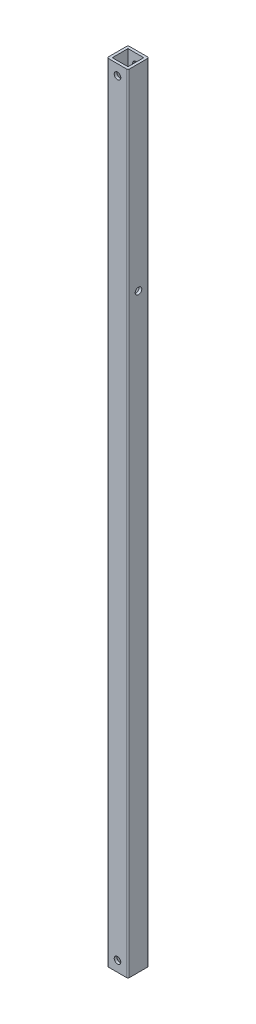
SolidWorks part; units mm, degrees
ref_plane "Front Plane" through (0, 0, 0) normal (0, 0, 1) x (1, 0, 0)
ref_plane "Top Plane" through (0, 0, 0) normal (0, 1, 0) x (1, 0, 0)
ref_plane "Right Plane" through (0, 0, 0) normal (1, 0, 0) x (0, 0, -1)
sketch "Sketch1" plane through (0, 0, 0) normal (0, 1, 0) x (1, 0, 0)
  line L0 (-2.7217, 3.211) -> (-2.7217, -8.789)
  line L1 (-4.7217, 5.211) -> (11.2783, 5.211)
  line L2 (-4.7217, 5.211) -> (-4.7217, -10.789)
  line L3 (-4.7217, -10.789) -> (11.2783, -10.789)
  line L4 (11.2783, 5.211) -> (11.2783, -10.789)
  line L5 (-2.7217, -8.789) -> (9.2783, -8.789)
  line L6 (9.2783, 3.211) -> (9.2783, -8.789)
  line L7 (-2.7217, 3.211) -> (9.2783, 3.211)
  dimension "D1" = 16
  dimension "D2" = 16
  dimension "D3" = 2
extrude "Boss-Extrude1" add sketch "Sketch1" along normal blind 600
fillet "Fillet1" radius 1 4 edges at (11.2783, 300, -5.211) (-4.7217, 300, -5.211) (-4.7217, 300, 10.789) (11.2783, 300, 10.789)
sketch "Sketch2" plane through (0, 0, 10.789) normal (0, 0, 1) x (1, 0, 0)
  line L0 (-3.7217, 600) -> (10.2783, 600) construction
  line L1 (-4.7217, 0) -> (-4.7217, 600) construction
  line L2 (-3.7217, 0) -> (10.2783, 0) construction
  circle A0 centre (3.2783, 592) radius 2.5
  circle A1 centre (3.2783, 8) radius 2.5
  dimension "D3" = 5
  dimension "D4" = 5
  dimension "D1" = 8
  dimension "D2" = 8
  dimension "D5" = 8
  dimension "D6" = 8
extrude "Cut-Extrude1" cut sketch "Sketch2" against normal blind 16
sketch "Sketch3" plane through (11.2783, 0, 0) normal (1, 0, 0) x (0, 0, -1)
  line L0 (5.211, 600) -> (5.211, 0) construction
  line L1 (-9.789, 600) -> (4.211, 600) construction
  circle A0 centre (-2.789, 450) radius 2.5
  dimension "D1" = 5
  dimension "D2" = 8
  dimension "D3" = 150
extrude "Cut-Extrude2" cut sketch "Sketch3" against normal blind 16
